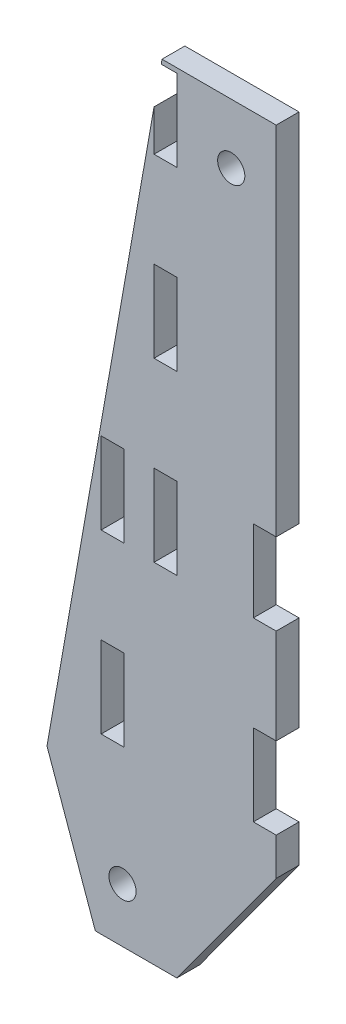
SolidWorks part; units mm, degrees
ref_plane "Front Plane" through (0, 0, 0) normal (0, 0, 1) x (1, 0, 0)
ref_plane "Top Plane" through (0, 0, 0) normal (0, 1, 0) x (1, 0, 0)
ref_plane "Right Plane" through (0, 0, 0) normal (1, 0, 0) x (0, 0, -1)
sketch "Sketch1" plane through (0, 0, 0) normal (0, 0, 1) x (1, 0, 0)
  line L0 (-80.8122, 105.4061) -> (-54.1422, 105.4061)
  line L1 (-96.3922, -78.7439) -> (-77.3422, -78.7439)
  line L2 (-96.3922, -78.7439) -> (-107.6845, -46.9939)
  line L4 (-54.1422, -46.9939) -> (-54.1422, 105.4061)
  line L6 (-107.6845, -46.9939) -> (-80.8122, 105.4061)
  line L9 (-77.3422, -78.7439) -> (-54.1422, -46.9939)
  dimension "D4" = 152.4
  dimension "D5" = 31.75
  dimension "D6" = 31.75
extrude "BodyShape" add sketch "Sketch1" along normal blind 5.334
sketch "Sketch2" plane through (0, 0, 5.334) normal (0, 0, 1) x (1, 0, 0)
  line L0 (-47.344, -46.9939) -> (-47.344, -38.2309) construction
  line L1 (-12.915, -38.2309) -> (-136.3936, -38.2309) construction
  line L2 (-54.1422, -46.9939) -> (-54.1422, 105.4061) construction
  line L3 (-54.1422, -38.2309) -> (-59.4762, -38.2309)
  line L4 (-54.1422, -38.2309) -> (-54.1422, -19.1809)
  line L5 (-54.1422, -19.1809) -> (-59.4762, -19.1809)
  line L6 (-59.4762, -38.2309) -> (-59.4762, -19.1809)
  line L7 (-54.1422, 3.0441) -> (-59.4762, 3.0441)
  line L8 (-54.1422, 3.0441) -> (-54.1422, 22.0941)
  line L9 (-54.1422, 22.0941) -> (-59.4762, 22.0941)
  line L10 (-59.4762, 3.0441) -> (-59.4762, 22.0941)
  line L11 (-89.7022, -38.2309) -> (-95.0362, -38.2309)
  line L12 (-89.7022, -38.2309) -> (-89.7022, -19.1809)
  line L13 (-89.7022, -19.1809) -> (-95.0362, -19.1809)
  line L14 (-95.0362, -38.2309) -> (-95.0362, -19.1809)
  line L15 (-89.7022, 3.0441) -> (-95.0362, 3.0441)
  line L16 (-89.7022, 3.0441) -> (-89.7022, 22.0941)
  line L17 (-89.7022, 22.0941) -> (-95.0362, 22.0941)
  line L18 (-95.0362, 3.0441) -> (-95.0362, 22.0941)
  dimension "D1" = 8.763
  dimension "D2" = 19.05
  dimension "D3" = 5.334
  dimension "D5" = 22.225
  dimension "D6" = 2
  dimension "D4" = 2
extrude "MotorMountCuts" cut sketch "Sketch2" against normal through all
sketch "Sketch3" plane through (0, 0, 5.334) normal (0, 0, 1) x (1, 0, 0)
  line L0 (-96.3922, -78.7439) -> (-96.3922, -66.0439) construction
  line L1 (-96.3922, -66.0439) -> (-90.0422, -66.0439) construction
  line L2 (-90.0422, -66.0439) -> (-64.6422, -66.0439) construction
  line L3 (-64.6422, -66.0439) -> (-64.6422, 91.4361) construction
  circle A0 centre (-90.0422, -66.0439) radius 3.175
  circle A1 centre (-64.6422, 91.4361) radius 3.175
  dimension "D3" = 6.35
  dimension "D6" = 6.35
  dimension "D1" = 12.7
  dimension "D2" = 6.35
  dimension "D4" = 25.4
  dimension "D5" = 157.48
extrude "BoltHoles" cut sketch "Sketch3" against normal through all
sketch "Sketch4" plane through (0, 0, 5.334) normal (0, 0, 1) x (1, 0, 0)
  line L0 (-177.2197, -78.7439) -> (15.1346, -78.7439) construction
  line L1 (-139.0483, -78.7439) -> (-139.0483, 12.5691) construction
  line L2 (-139.0483, 12.5691) -> (-139.0483, 104.296) construction
  line L3 (-54.1422, 125.2357) -> (-82.6762, 125.2357) construction
  line L4 (-82.6762, 104.296) -> (-77.3422, 104.296)
  line L5 (-77.3422, 104.296) -> (-77.3422, 85.246)
  line L6 (-77.3422, 85.246) -> (-82.6762, 85.246)
  line L7 (-82.6762, 85.246) -> (-82.6762, 104.296)
  line L8 (-82.6762, 122.006) -> (-82.6762, -97.2437) construction
  line L9 (-48.7336, 85.246) -> (-48.7336, 63.021) construction
  line L10 (-48.7336, 43.971) -> (-48.7336, 21.746) construction
  line L11 (-82.6762, 63.021) -> (-77.3422, 63.021)
  line L12 (-82.6762, 63.021) -> (-82.6762, 43.971)
  line L13 (-82.6762, 43.971) -> (-77.3422, 43.971)
  line L14 (-77.3422, 63.021) -> (-77.3422, 43.971)
  line L16 (-82.6762, 21.746) -> (-77.3422, 21.746)
  line L17 (-82.6762, 21.746) -> (-82.6762, 2.696)
  line L18 (-82.6762, 2.696) -> (-77.3422, 2.696)
  line L19 (-77.3422, 21.746) -> (-77.3422, 2.696)
  dimension "D1" = 91.313
  dimension "D2" = 91.727
  dimension "D3" = 28.534
  dimension "D4" = 5.334
  dimension "D5" = 19.05
  dimension "D6" = 22.225
  dimension "D7" = 19.05
  dimension "D8" = 22.225
  dimension "D9" = 19.05
extrude "Cut-Extrude3" cut sketch "Sketch4" against normal through all
